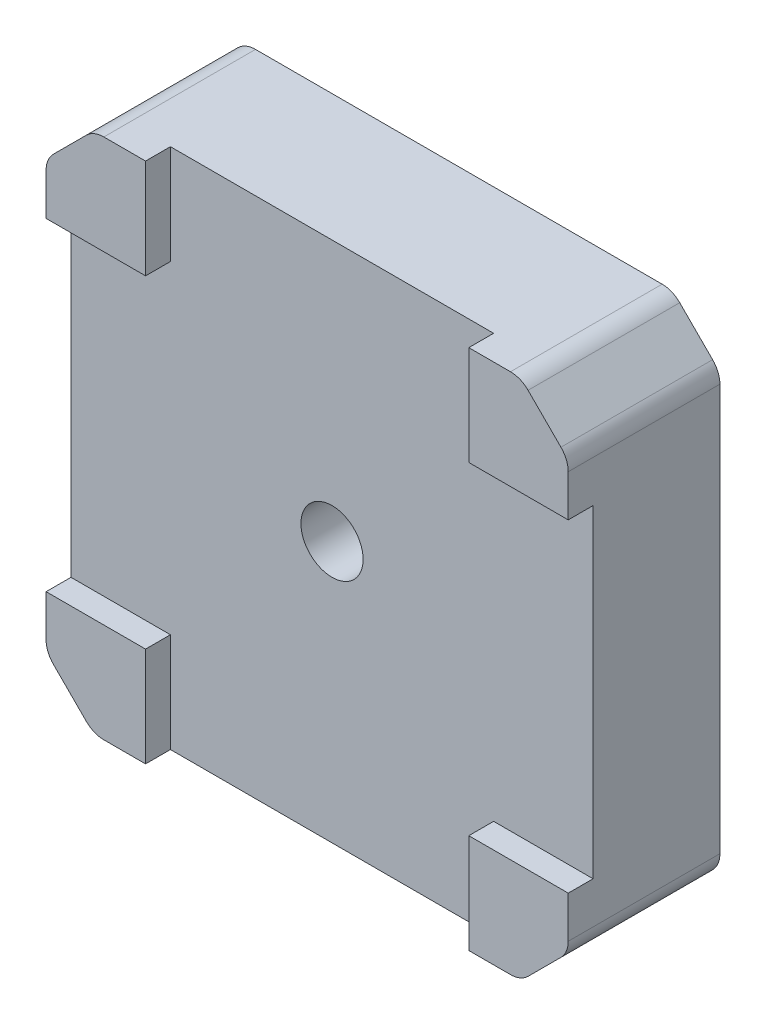
SolidWorks part; units mm, degrees
material "Alumina"
ref_plane "Front" through (0, 0, 0) normal (0, 0, 1) x (1, 0, 0)
ref_plane "Top" through (0, 0, 0) normal (0, 1, 0) x (1, 0, 0)
ref_plane "Right" through (0, 0, 0) normal (1, 0, 0) x (0, 0, -1)
sketch "Sketch1" plane through (0, 0, 0) normal (0, 0, 1) x (1, 0, 0)
  line L0 (-17.1838, 21) -> (-21, 17.1838)
  line L1 (-17.1838, -21) -> (17.1838, -21)
  line L2 (-21, -17.1838) -> (-21, 17.1838)
  line L3 (-17.1838, 21) -> (17.1838, 21)
  line L4 (21, -17.1838) -> (21, 17.1838)
  line L5 (-19.0919, 19.0919) -> (19.0919, -19.0919) construction
  line L6 (19.0919, 19.0919) -> (-19.0919, -19.0919) construction
  line L7 (0, -21) -> (0, 21) construction
  line L8 (-21, 0) -> (21, 0) construction
  line L9 (17.1838, 21) -> (21, 17.1838)
  line L10 (17.1838, -21) -> (21, -17.1838)
  line L11 (-17.1838, -21) -> (-21, -17.1838)
  point P0 (0, 0)
  dimension "D1" = 42
  dimension "D2" = 42
  dimension "D3" = 54
extrude "Boss-Extrude1" add sketch "Sketch1" along normal blind 12.2
sketch "Sketch2" plane through (21, 0, 0) normal (1, 0, 0) x (0, 0, -1)
  line L0 (-12.2, -17.1838) -> (-12.2, 17.1838) construction
  line L1 (-12.2, 13) -> (-10.2, 13)
  line L2 (-12.2, 13) -> (-12.2, -13)
  line L3 (-12.2, -13) -> (-10.2, -13)
  line L4 (-10.2, 13) -> (-10.2, -13)
  line L7 (0, 0) -> (-12.2, 0) construction
  line L8 (0, -17.1838) -> (0, 17.1838) construction
  dimension "D1" = 2
  dimension "D2" = 26
extrude "Cut-Extrude1" cut sketch "Sketch2" against normal through all
sketch "Sketch3" plane through (0, 21, 0) normal (0, 1, 0) x (1, 0, 0)
  line L0 (17.1838, -12.2) -> (-17.1838, -12.2) construction
  line L1 (-13, -12.2) -> (13, -12.2)
  line L2 (-13, -12.2) -> (-13, -10.2)
  line L3 (-13, -10.2) -> (13, -10.2)
  line L4 (13, -12.2) -> (13, -10.2)
  line L7 (0, 0) -> (0, -12.2) construction
  line L8 (17.1838, 0) -> (-17.1838, 0) construction
  dimension "D1" = 2
  dimension "D2" = 26
extrude "Cut-Extrude2" cut sketch "Sketch3" against normal through all
sketch "Sketch4" plane through (0, 0, 0) normal (0, 0, -1) x (-1, 0, 0)
  circle A0 centre (0, 0) radius 16.5
  dimension "D1" = 33
extrude "Cut-Extrude3" cut sketch "Sketch4" against normal blind 0.6
sketch "Sketch5" plane through (0, 0, 0.6) normal (0, 0, -1) x (-1, 0, 0)
  circle A0 centre (0, 0) radius 11
  dimension "D1" = 22
extrude "Boss-Extrude2" add sketch "Sketch5" along normal blind 2.6
sketch "Sketch6" plane through (0, 0, -2) normal (0, 0, -1) x (-1, 0, 0)
  circle A0 centre (0, 0) radius 3.25
  dimension "D1" = 6.5
extrude "Cut-Extrude4" cut sketch "Sketch6" against normal blind 2
sketch "Sketch7" plane through (0, 0, 0) normal (0, 0, -1) x (-1, 0, 0)
  circle A0 centre (0, 0) radius 2.5
  dimension "D1" = 5
extrude "Cut-Extrude5" cut sketch "Sketch7" against normal through all
fillet "Fillet1" radius 0.5 1 edges at (-3.25, 0, -2)
fillet "Fillet3" radius 0.5 1 edges at (-11, 0, 0.6)
fillet "Fillet4" radius 2 8 edges at (21, 17.1838, 6.1) (17.1838, 21, 6.1) (-17.1838, 21, 6.1) (-21, 17.1838, 6.1) (-21, -17.1838, 6.1) (-17.1838, -21, 6.1) (17.1838, -21, 6.1) (21, -17.1838, 6.1)
hole_wizard "M3x0.5 Tapped Hole1" positions "Sketch9" profile "Sketch8" tap size "M3x0.5" standard "ANSI Metric"
sketch "Sketch9" plane through (0, 0, 0) normal (0, 0, -1) x (-1, 0, 0)
  line L0 (0, 0) -> (-21, 0) construction
  line L1 (-21, -16.3553) -> (-21, 16.3553) construction
  line L2 (0, 0) -> (0, 21) construction
  line L3 (-16.3553, 21) -> (16.3553, 21) construction
  point P0 (-15.5, -15.5)
  point P9 (-15.5, 15.5)
  point P17 (15.5, 15.5)
  point P18 (15.5, -15.5)
  dimension "D1" = 31
  dimension "D2" = 31
sketch "Sketch8" plane through (15.5, -15.5, 0) normal (1, 0, 0) x (0, 1, 0)
  line L0 (0, 0) -> (0, 10.7511)
  line L1 (0, 10.7511) -> (1.25, 10)
  line L2 (1.25, 10) -> (1.25, 0.5)
  line L3 (1.25, 0.5) -> (1.75, 0)
  line L5 (1.75, 0) -> (0, 0)
  line L6 (-1.25, 0.5) -> (-1.75, 0) construction
  line L10 (0, 10.7511) -> (-1.25, 10) construction
  line L11 (0, -6.35) -> (0, 107.95) construction
  dimension "Tap Drill Dia." = 2.5
  dimension "Tap Drill Depth" = 10
  dimension "Near C'Sink Dia." = 3.5
  dimension "Near C'Sink Angle" = 90
  dimension "Drill Angle" = 118
